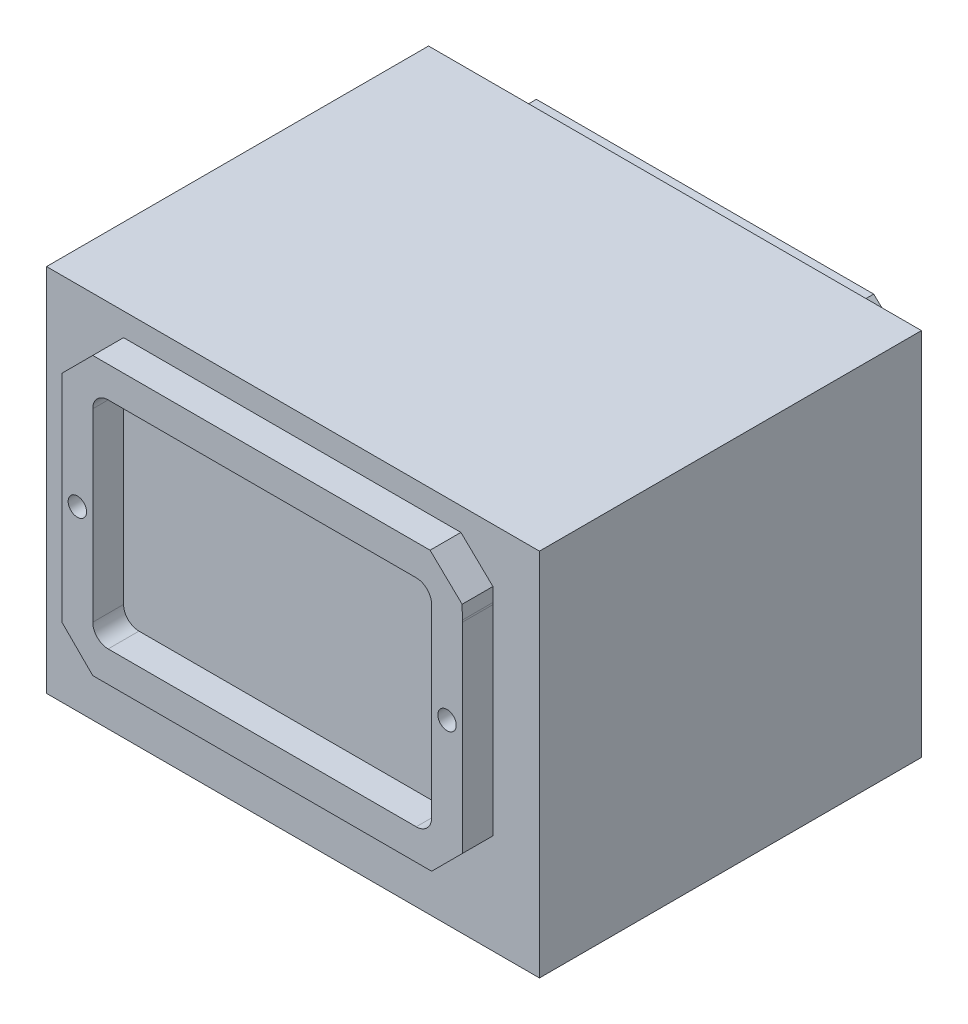
SolidWorks part; units mm, degrees
ref_plane "Front Plane" through (0, 0, 0) normal (0, 0, 1) x (1, 0, 0)
ref_plane "Top Plane" through (0, 0, 0) normal (0, 1, 0) x (1, 0, 0)
ref_plane "Right Plane" through (0, 0, 0) normal (1, 0, 0) x (0, 0, -1)
sketch "Sketch1" plane through (0, 0, 0) normal (0, 1, 0) x (1, 0, 0)
  line L1 (0, 0) -> (101.6, 0)
  line L2 (0, 0) -> (0, 76.2)
  line L3 (0, 76.2) -> (101.6, 76.2)
  line L4 (101.6, 0) -> (101.6, 76.2)
  dimension "D1" = 101.6
  dimension "D2" = 76.2
extrude "Extrude1" add sketch "Sketch1" against normal blind 76.2
sketch "Sketch2" plane through (0, 0, 0) normal (0, 1, 0) x (1, 0, 0)
  line L0 (50.8, 0) -> (50.8, 76.2) construction
  line L1 (0, 0) -> (101.6, 0) construction
  line L2 (101.6, 76.2) -> (0, 76.2) construction
  line L4 (23.5431, 57.2721) -> (80.6931, 57.2721)
  line L5 (20.3681, 54.0971) -> (20.3681, 22.3471)
  line L6 (23.5431, 19.1721) -> (80.6931, 19.1721)
  line L7 (83.8681, 54.0971) -> (83.8681, 22.3471)
  line L11 (23.5431, 63.6221) -> (80.6931, 63.6221)
  line L12 (90.2181, 54.0971) -> (90.2181, 22.3471)
  line L13 (23.5431, 12.8221) -> (80.6931, 12.8221)
  line L14 (14.0181, 54.0971) -> (14.0181, 22.3471)
  arc A0 (23.5431, 57.2721) -> (20.3681, 54.0971) centre (23.5431, 54.0971) ccw
  arc A1 (20.3681, 22.3471) -> (23.5431, 19.1721) centre (23.5431, 22.3471) ccw
  arc A2 (80.6931, 57.2721) -> (83.8681, 54.0971) centre (80.6931, 54.0971) cw
  arc A3 (80.6931, 19.1721) -> (83.8681, 22.3471) centre (80.6931, 22.3471) ccw
  arc A8 (80.6931, 63.6221) -> (90.2181, 54.0971) centre (80.6931, 54.0971) cw
  arc A9 (80.6931, 12.8221) -> (90.2181, 22.3471) centre (80.6931, 22.3471) ccw
  arc A10 (14.0181, 22.3471) -> (23.5431, 12.8221) centre (23.5431, 22.3471) ccw
  arc A11 (23.5431, 63.6221) -> (14.0181, 54.0971) centre (23.5431, 54.0971) ccw
  point P6 (50.8, 38.1)
  dimension "D1" = 76.2
  dimension "D4" = 3.175
  dimension "D2" = 63.5
  dimension "D3" = 38.1
  dimension "D7" = 6.35
sketch "Sketch3" plane through (0, 0, 0) normal (0, 0, 1) x (1, 0, 0)
  line L0 (50.8, -76.2) -> (50.8, 0) construction
  line L1 (19.05, -4.7544) -> (82.55, -4.7544)
  line L2 (0, -76.2) -> (101.6, -76.2) construction
  line L3 (92.075, -14.2794) -> (92.075, -52.3794)
  line L4 (19.05, -11.1044) -> (82.55, -11.1044)
  line L5 (15.875, -14.2794) -> (15.875, -52.3794)
  line L6 (19.05, -55.5544) -> (82.55, -55.5544)
  line L7 (85.725, -14.2794) -> (85.725, -52.3794)
  line L8 (19.05, -61.9044) -> (82.55, -61.9044)
  line L9 (9.525, -14.2794) -> (9.525, -52.3794)
  arc A0 (19.05, -11.1044) -> (15.875, -14.2794) centre (19.05, -14.2794) ccw
  arc A1 (82.55, -11.1044) -> (85.725, -14.2794) centre (82.55, -14.2794) cw
  arc A2 (82.55, -55.5544) -> (85.725, -52.3794) centre (82.55, -52.3794) ccw
  arc A3 (15.875, -52.3794) -> (19.05, -55.5544) centre (19.05, -52.3794) ccw
  arc A4 (82.55, -4.7544) -> (92.075, -14.2794) centre (82.55, -14.2794) cw
  arc A5 (82.55, -61.9044) -> (92.075, -52.3794) centre (82.55, -52.3794) ccw
  arc A6 (9.525, -52.3794) -> (19.05, -61.9044) centre (19.05, -52.3794) ccw
  arc A7 (19.05, -4.7544) -> (9.525, -14.2794) centre (19.05, -14.2794) ccw
  point P4 (50.8, -38.1)
  dimension "D1" = 3.175
  dimension "D2" = 6.35
extrude "Extrude2" add sketch "Sketch3" along normal blind 6.35
ref_plane "Plane1" through (16.8049, -12.0344, 6.35) normal (0, 0, 1) x (1, 0, 0)
sketch "Sketch4" plane through (16.8049, -12.0344, 6.35) normal (0, 0, 1) x (1, 0, 0)
  line L0 (-0.9299, -21.2951) -> (-7.2799, -21.2951) construction
  line L1 (-0.9299, -2.2451) -> (-0.9299, -40.3451) construction
  line L2 (-7.2799, -2.2451) -> (-7.2799, -40.3451) construction
  line L3 (68.9201, -21.2951) -> (75.2701, -21.2951) construction
  line L4 (68.9201, -40.3451) -> (68.9201, -2.2451) construction
  line L5 (75.2701, -40.3451) -> (75.2701, -2.2451) construction
hole_wizard "#10-24 Tapped Hole1" positions "3DSketch1" profile "Sketch5" tap size "#10-24" standard "Ansi Inch"
sketch3d "3DSketch1"
  line L0 (15.875, -33.3294, 6.35) -> (9.525, -33.3294, 6.35) construction
  line L1 (85.725, -33.3294, 6.35) -> (92.075, -33.3294, 6.35) construction
  point P0 (12.7, -33.3294, 6.35)
  point P4 (88.9, -33.3294, 6.35)
  point P10 (12.7, -33.3294, 6.35)
  point P12 (88.9, -33.3294, 6.35)
sketch "Sketch5" plane through (12.7, -33.3294, 6.35) normal (1, 0, 0) x (0, -1, 0)
  line L0 (0, 0) -> (0, 14.0948)
  line L1 (0, 14.0948) -> (1.8986, 12.954)
  line L2 (1.8986, 12.954) -> (1.8986, 0)
  line L5 (1.8986, 0) -> (0, 0)
  line L10 (0, 14.0948) -> (-1.8987, 12.954) construction
  line L11 (0, -6.35) -> (0, 107.95) construction
  dimension "Tap Drill Dia." = 3.7973
  dimension "Tap Drill Depth" = 12.954
  dimension "Drill Angle" = 118
cosmetic thread "Hole Thread1" parameters "D1"=9.652, "D2"=4.826
cosmetic thread "Hole Thread2" parameters "D1"=9.652, "D2"=4.826
cosmetic thread "Hole Thread3" parameters "D1"=9.652, "D2"=4.826
cosmetic thread "Hole Thread4" parameters "D1"=9.652, "D2"=4.826
sketch "Sketch6" plane through (0, 0, 0) normal (0, 0, 1) x (1, 0, 0)
  line L0 (82.55, -4.7544) -> (91.8859, -4.7544)
  line L1 (91.8859, -4.7544) -> (92.075, -14.2794)
  line L2 (92.075, -14.2794) -> (82.55, -4.7544)
  line L3 (92.075, -52.3794) -> (82.55, -61.9044)
  line L4 (82.55, -61.9044) -> (92.075, -61.9044)
  line L5 (92.075, -61.9044) -> (92.075, -52.3794)
  line L6 (9.525, -14.2794) -> (19.05, -4.7544)
  line L7 (19.05, -4.7544) -> (9.525, -4.7544)
  line L8 (9.525, -4.7544) -> (9.525, -14.2794)
  line L9 (9.525, -52.3794) -> (19.05, -61.9044)
  line L10 (19.05, -61.9044) -> (9.525, -61.9044)
  line L11 (9.525, -61.9044) -> (9.525, -52.3794)
extrude "Extrude3" add sketch "Sketch6" along normal blind 6.35
chamfer "Chamfer1" distance 6.35 angle 45 4 edges at (92.075, -61.9044, 3.175) (9.525, -61.9044, 3.175) (9.525, -4.7544, 3.175) (91.8859, -4.7544, 3.175)
ref_plane "Plane2" through (0, 0, -78.74) normal (0, 0, -1) x (-1, 0, 0)
sketch "Sketch7" plane through (0, 0, -78.74) normal (0, 0, -1) x (-1, 0, 0)
  line L0 (-85.4061, -4.7544) -> (-15.875, -4.7544)
  line L1 (-85.725, -61.9044) -> (-15.875, -61.9044)
  line L2 (-92.075, -11.1031) -> (-92.075, -55.5544)
  line L4 (-15.875, -4.7544) -> (-9.525, -11.1044)
  line L5 (-15.875, -61.9044) -> (-9.525, -55.5544)
  line L6 (-85.725, -61.9044) -> (-92.075, -55.5544)
  line L7 (-92.075, -11.1031) -> (-85.4061, -4.7544)
  line L8 (-15.875, -14.4064) -> (-15.875, -52.2524)
  line L9 (-82.423, -55.5544) -> (-19.177, -55.5544)
  line L10 (-85.725, -14.4064) -> (-85.725, -52.2524)
  line L11 (-82.423, -11.1044) -> (-19.177, -11.1044)
  line L12 (-9.525, -55.5544) -> (-9.525, -11.1044)
  arc A2 (-19.177, -55.5544) -> (-15.875, -52.2524) centre (-19.177, -52.2524) ccw
  arc A3 (-85.725, -52.2524) -> (-82.423, -55.5544) centre (-82.423, -52.2524) ccw
  arc A4 (-85.725, -14.4064) -> (-82.423, -11.1044) centre (-82.423, -14.4064) cw
  arc A5 (-15.875, -14.4064) -> (-19.177, -11.1044) centre (-19.177, -14.4064) ccw
  dimension "D1" = 3.302
extrude "Extrude4" add sketch "Sketch7" along normal blind 6.35
ref_plane "Plane3" through (0, 0, -76.2) normal (0, 0, -1) x (-1, 0, 0)
sketch "Sketch8" plane through (0, 0, -76.2) normal (0, 0, -1) x (-1, 0, 0)
  line L1 (-101.6, 0) -> (0, 0)
  line L2 (-101.6, 0) -> (-101.6, -76.2)
  line L3 (-101.6, -76.2) -> (0, -76.2)
  line L4 (0, 0) -> (0, -76.2)
extrude "Extrude5" add sketch "Sketch8" along normal blind 2.54
ref_plane "Plane4" through (0, 0, -85.09) normal (0, 0, -1) x (-1, 0, 0)
sketch "Sketch9" plane through (0, 0, -85.09) normal (0, 0, -1) x (-1, 0, 0)
  line L3 (-15.875, -33.3294) -> (-9.525, -33.3294) construction
  line L4 (-15.875, -52.2524) -> (-15.875, -14.4064) construction
  line L5 (-9.525, -52.3794) -> (-9.525, -14.2794) construction
  line L6 (-92.075, -33.3288) -> (-85.725, -33.3294) construction
  line L7 (-92.075, -11.1031) -> (-92.075, -55.5544) construction
  line L8 (-85.725, -14.4064) -> (-85.725, -52.2524) construction
  point P12 (-12.7, -33.3294)
hole_wizard "#10-24 Tapped Hole2" positions "3DSketch2" profile "Sketch10" tap size "#10-24" standard "Ansi Inch"
sketch3d "3DSketch2"
  line L0 (92.075, -33.3294, -85.09) -> (85.725, -33.3294, -85.09) construction
  point P0 (88.9, -33.3294, -85.09)
  point P4 (88.9, -33.3294, -85.09)
  point P6 (12.7, -33.3294, -85.09)
sketch "Sketch10" plane through (88.9, -33.3294, -85.09) normal (1, 0, 0) x (0, 1, 0)
  line L0 (0, 0) -> (0, 14.0948)
  line L1 (0, 14.0948) -> (1.8986, 12.954)
  line L2 (1.8986, 12.954) -> (1.8986, 9.652)
  line L3 (1.8986, 9.652) -> (2.413, 9.652)
  line L4 (2.413, 9.652) -> (2.413, 0)
  line L5 (2.413, 0) -> (0, 0)
  line L10 (0, 14.0948) -> (-1.8987, 12.954) construction
  line L11 (0, -6.35) -> (0, 107.95) construction
  dimension "Tap Drill Dia." = 3.7973
  dimension "Tap Drill Depth" = 12.954
  dimension "Thread Major Dia." = 4.826
  dimension "Thread Depth" = 9.652
  dimension "Drill Angle" = 118
